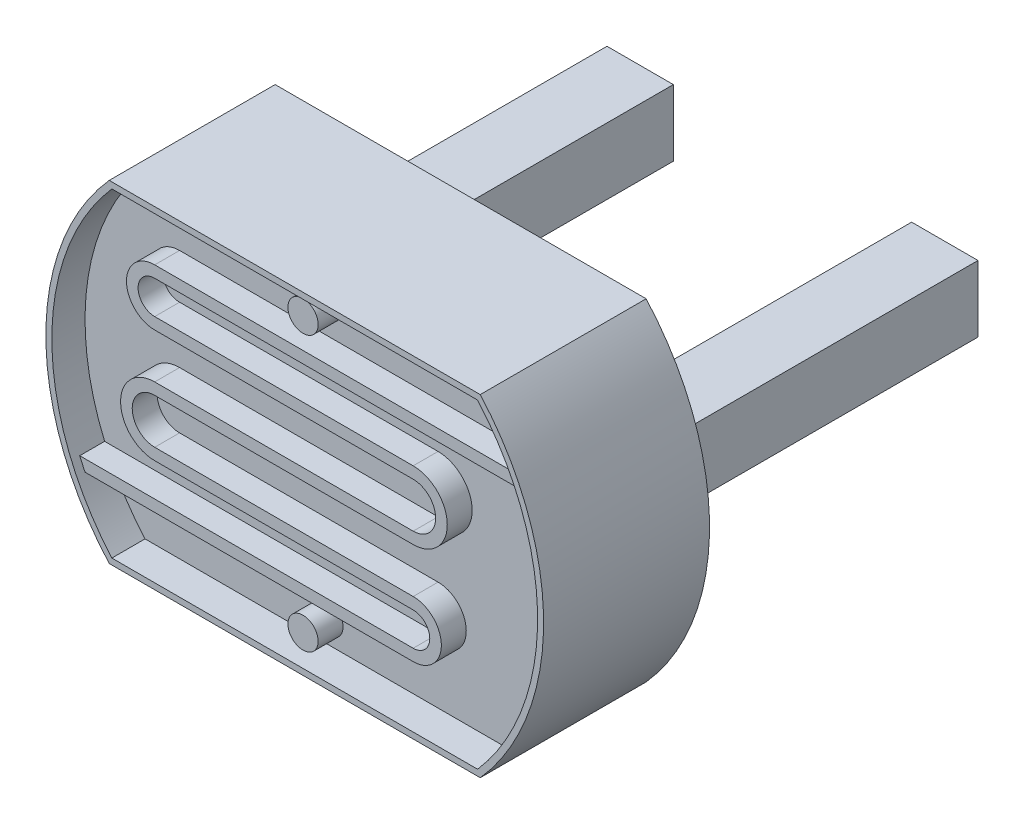
SolidWorks part; units mm, degrees
ref_plane "Front Plane" through (0, 0, 0) normal (0, 0, 1) x (1, 0, 0)
ref_plane "Top Plane" through (0, 0, 0) normal (0, 1, 0) x (1, 0, 0)
ref_plane "Right Plane" through (0, 0, 0) normal (1, 0, 0) x (0, 0, -1)
sketch "Sketch1" plane through (0, 0, 0) normal (0, 0, 1) x (1, 0, 0)
  line L0 (-11.1803, 10) -> (11.1803, 10)
  line L1 (11.1803, -10) -> (-11.1803, -10)
  arc A0 (-11.1803, 10) -> (-11.1803, -10) centre (0, 0) ccw
  arc A1 (11.1803, -10) -> (11.1803, 10) centre (0, 0) ccw
  dimension "D1" = 30
extrude "Boss-Extrude1" add sketch "Sketch1" along normal blind 8
sketch "Sketch2" plane through (0, 0, 0) normal (0, 0, -1) x (-1, 0, 0)
  line L3 (11.1803, -2) -> (11.1803, 0) construction
  line L4 (-11.1803, 2) -> (-11.1803, -2)
  line L8 (7.1803, 2) -> (7.1803, -2)
  line L9 (11.1803, 0) -> (11.1803, 2)
  line L10 (-11.1803, -2) -> (-11.1803, 2) construction
  line L14 (-7.1803, -2) -> (-7.1803, 2)
  line L15 (11.1803, 0) -> (11.1803, -2)
  line L16 (11.1803, 2) -> (7.1803, 2)
  line L18 (4.4, 0) -> (-4.4, 0) construction
  line L19 (11.1803, -2) -> (7.1803, -2)
  line L20 (-7.1803, -2) -> (-11.1803, -2)
  line L21 (-7.1803, 2) -> (-11.1803, 2)
  point P6 (11.1803, 0)
  point P13 (-11.1803, 0)
  dimension "D3" = 2
extrude "Boss-Extrude2" add sketch "Sketch2" along normal blind 20
sketch "Sketch3" plane through (0, 0, 8) normal (0, 0, 1) x (1, 0, 0)
  line L0 (-11.1803, 10) -> (11.1803, 10)
  line L1 (-11.1803, -10) -> (11.1803, -10)
  line L2 (11.0214, -9.6342) -> (-11.0214, -9.6342)
  line L3 (15.4, 0) -> (-15.4, 0) construction
  line L4 (11.0214, 9.6342) -> (-11.0214, 9.6342)
  arc A0 (11.1803, -10) -> (11.1803, 10) centre (0, 0) ccw
  arc A1 (11.0214, -9.6342) -> (11.0214, 9.6342) centre (0, 0) ccw
  arc A2 (-11.1803, 10) -> (-11.1803, -10) centre (0, 0) ccw
  arc A3 (-11.0214, 9.6342) -> (-11.0214, -9.6342) centre (0, 0) ccw
  arc M9 (11.1803, -10) -> (11.1803, 10) centre (0, 0) ccw
  line M10 (11.1803, 10) -> (-11.1803, 10)
  arc M11 (-11.1803, 10) -> (-11.1803, -10) centre (0, 0) ccw
  line M12 (-11.1803, -10) -> (11.1803, -10)
extrude "Boss-Extrude3" add sketch "Sketch3" along normal blind 2 contours A3 L4 A1 L2 M12 M9 M10 M11
sketch "Sketch4" plane through (0, 0, 8) normal (0, 0, 1) x (1, 0, 0)
  line L0 (13.1358, 6.4607) -> (-8.94, 6.4607)
  line L1 (13.4575, 5.7607) -> (-8.94, 5.7607)
  line L2 (-8.94, 3.7607) -> (6.6381, 3.7607)
  line L3 (-8.94, 0.35) -> (6.6381, 0.35)
  line L4 (6.6381, 3.0607) -> (-8.94, 3.0607)
  line L5 (16.5, 0) -> (-16.5, 0) construction
  line L6 (6.6381, -6.4607) -> (-8.94, -6.4607)
  line L7 (6.6381, -5.7607) -> (-8.94, -5.7607)
  line L8 (-8.94, -3.7607) -> (6.6381, -3.7607)
  line L9 (6.6381, -3.0607) -> (-8.94, -3.0607)
  line L10 (-8.94, -5.7607) -> (-13.4575, -5.7607)
  line L11 (-8.94, -6.4607) -> (-13.1358, -6.4607)
  line L12 (-8.94, -0.35) -> (6.6381, -0.35)
  arc A0 (11.0214, -9.6342) -> (11.0214, 9.6342) centre (0, 0) ccw construction
  arc A1 (-11.0214, 9.6342) -> (-11.0214, -9.6342) centre (0, 0) ccw construction
  arc A2 (6.6381, -3.0607) -> (6.6381, -6.4607) centre (6.6381, -4.7607) cw
  arc A3 (6.6381, -3.7607) -> (6.6381, -5.7607) centre (6.6381, -4.7607) cw
  arc A4 (-8.94, -0.35) -> (-8.94, -3.0607) centre (-8.94, -1.7053) ccw
  arc A5 (-8.94, 0.35) -> (-8.94, -3.7607) centre (-8.94, -1.7053) ccw
  arc A6 (6.6381, 0.35) -> (6.6381, 3.0607) centre (6.6381, 1.7053) ccw
  arc A7 (6.6381, -0.35) -> (6.6381, 3.7607) centre (6.6381, 1.7053) ccw
  arc A8 (-8.94, 5.7607) -> (-8.94, 3.7607) centre (-8.94, 4.7607) ccw
  arc A9 (-8.94, 3.0607) -> (-8.94, 6.4607) centre (-8.94, 4.7607) cw
  arc A10 (13.1358, 6.4607) -> (13.4575, 5.7607) centre (0, 0) cw
  arc A11 (-13.4575, -5.7607) -> (-13.1358, -6.4607) centre (0, 0) ccw
  circle A12 centre (0, 8.2669) radius 0.9111
  circle A13 centre (0, -8.2669) radius 0.9111
  dimension "D1" = 2
  dimension "D2" = 0.7
  dimension "D3" = 0.7
  dimension "D4" = 0.7
extrude "Boss-Extrude4" add sketch "Sketch4" along normal blind 1.5
